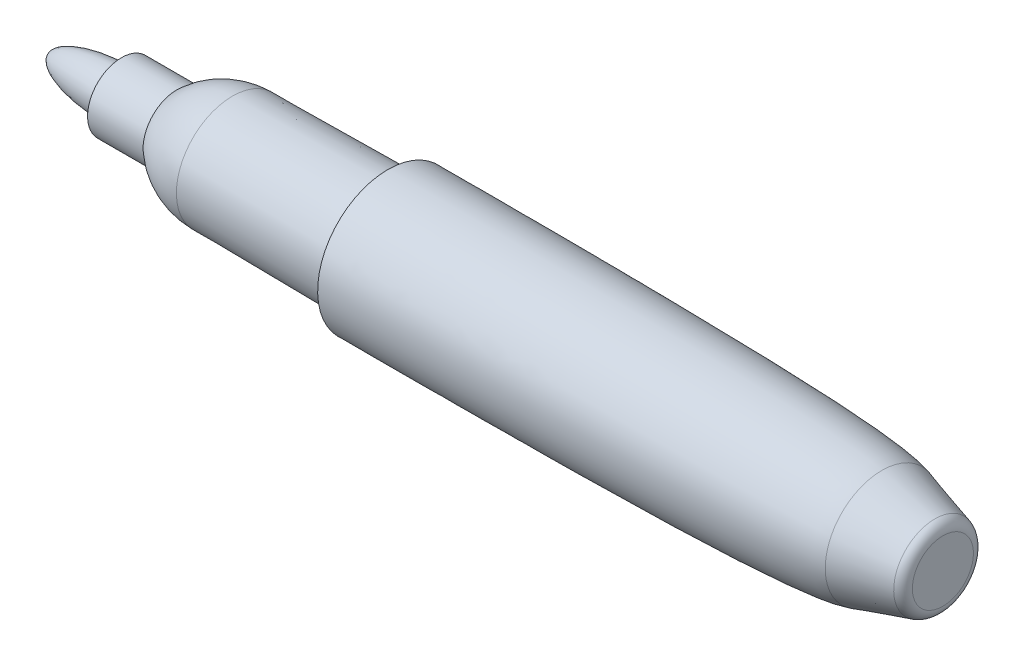
SolidWorks part; units mm, degrees
material "ABS PC"
ref_plane "Front Plane" through (0, 0, 0) normal (0, 0, 1) x (1, 0, 0)
ref_plane "Top Plane" through (0, 0, 0) normal (0, 1, 0) x (1, 0, 0)
ref_plane "Right Plane" through (0, 0, 0) normal (1, 0, 0) x (0, 0, -1)
sketch "Sketch1" plane through (0, 0, 0) normal (0, 0, 1) x (1, 0, 0)
  line L0 (0, 0) -> (-80.5, 0)
  line L1 (-74, 2) -> (-74, 3.05)
  line L2 (-74, 3.05) -> (-69, 3.05)
  line L3 (-64, 5.05) -> (-50, 5.2)
  line L4 (-50, 5.2) -> (-50, 6.325)
  line L5 (0, 0) -> (0, 2.75)
  line L6 (-0.7208, 3.7102) -> (-5.5, 5.1)
  arc A0 (-64, 5.05) -> (-69, 3.05) centre (-63.9202, -2.3995) ccw
  arc A1 (0, 2.75) -> (-0.7208, 3.7102) centre (-1, 2.75) ccw
  ellipse E0 centre (-74, 0) end of major axis (-80.5, 0) minor radius 2 (-74, 2) -> (-80.5, 0) ccw
  spline S0 degree 3 poles (-50, 6.325) (-26.9364, 6.325) (-9.3473, 6.2188) (-5.5, 5.1) knots 0 0 0 0 0.97047 0.97047 0.97047 0.97047
  dimension "D10" = 1
  dimension "D11" = 50
  dimension "D1" = 6.5
  dimension "D2" = 2
  dimension "D3" = 3.05
  dimension "D4" = 5
  dimension "D5" = 5.05
  dimension "D6" = 5.2
  dimension "D7" = 14
  dimension "D8" = 24
  dimension "D9" = 6.325
  dimension "D12" = 2.75
  dimension "D13" = 5.5
  dimension "D14" = 5.1
revolve "Revolve1" add sketch "Sketch1" angle 360 about L0
